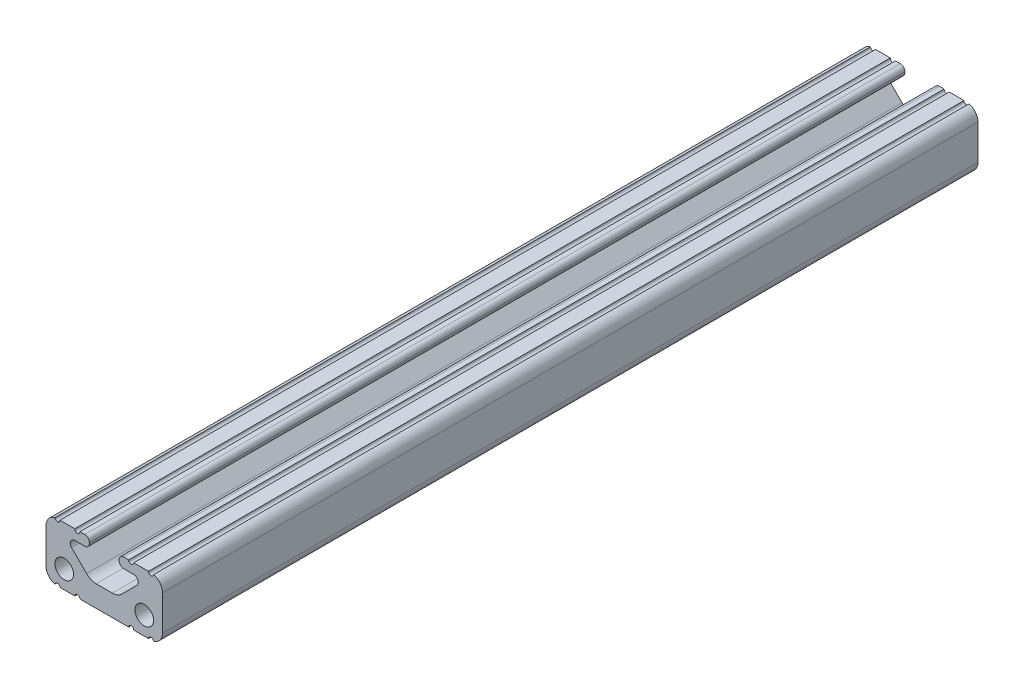
SolidWorks part; units mm, degrees
ref_plane "Front Plane" through (0, 0, 0) normal (0, 0, 1) x (1, 0, 0)
ref_plane "Top Plane" through (0, 0, 0) normal (0, 1, 0) x (1, 0, 0)
ref_plane "Right Plane" through (0, 0, 0) normal (1, 0, 0) x (0, 0, -1)
sketch "Sketch1" plane through (0, 0, 0) normal (0, 0, 1) x (1, 0, 0)
  line L0 (0, 6.35) -> (0, -6.35) construction
  line L1 (0, -6.35) -> (12.7, -6.35)
  line L2 (12.7, -6.35) -> (12.7, 6.35)
  line L3 (12.7, 6.35) -> (3.2512, 6.35)
  line L4 (3.2512, 6.35) -> (3.2512, 4.1402)
  line L5 (3.2512, 4.1402) -> (6.4224, 4.1402)
  line L6 (7.1255, 2.4426) -> (2.9811, -1.7018)
  line L7 (2.9811, -1.7018) -> (0, -1.7018)
  circle A0 centre (8.7249, -2.3876) radius 2.032
  arc A1 (6.4224, 4.1402) -> (7.1255, 2.4426) centre (6.4224, 3.1458) cw
  dimension "Center Hole Diameter" = 4.064
  dimension "D3" = 0.9944
  dimension "Rail Height" = 25.4
  dimension "Rail Width" = 12.7
  dimension "Hole CtoC" = 17.4498
  dimension "D1" = 3.9624
  dimension "T-Slot Width" = 6.5024
  dimension "Thickness" = 2.2098
  dimension "Inner Slot Width" = 14.8336
  dimension "Slot Depth" = 5.842
  dimension "D2" = 45
sketch "Sketch2" plane through (0, 0, 0) normal (1, 0, 0) x (0, 0, -1)
  line L0 (-152.4, -6.35) -> (152.4, -6.35) construction
  line L1 (-127, 0) -> (127, 0) construction
  dimension "Length" = 304.8
sketch "Sketch3" plane through (0, 0, 0) normal (0, 0, 1) x (1, 0, 0)
  line L0 (3.2512, 6.35) -> (3.2512, 4.1402) construction
  line L1 (12.7, 6.35) -> (3.2512, 6.35) construction
  line L2 (3.2512, 4.1402) -> (6.4224, 4.1402) construction
  line L3 (3.2512, 5.3556) -> (3.2512, 5.1346)
  line L4 (12.7, -6.35) -> (12.7, 6.35) construction
  line L5 (0, -6.35) -> (12.7, -6.35) construction
  line L6 (2.9811, -1.7018) -> (0, -1.7018) construction
  line L7 (7.1255, 2.4426) -> (2.9811, -1.7018) construction
  line L8 (0, -1.7018) -> (1.7454, -1.7018)
  line L9 (4.2456, 4.1402) -> (6.4224, 4.1402)
  line L10 (3.8549, -0.828) -> (7.1255, 2.4426)
  line L11 (0, -1.7018) -> (0, -6.35)
  line L12 (0, -6.35) -> (10.16, -6.35)
  line L13 (12.7, -3.81) -> (12.7, 3.81)
  line L14 (4.2456, 6.35) -> (10.16, 6.35)
  arc A0 (3.2512, 5.3556) -> (4.2456, 6.35) centre (4.2456, 5.3556) cw
  arc A1 (3.2512, 5.1346) -> (4.2456, 4.1402) centre (4.2456, 5.1346) ccw
  arc A2 (7.1255, 2.4426) -> (6.4224, 4.1402) centre (6.4224, 3.1458) ccw construction
  arc A3 (10.16, 6.35) -> (12.7, 3.81) centre (10.16, 3.81) cw
  arc A4 (10.16, -6.35) -> (12.7, -3.81) centre (10.16, -3.81) ccw
  arc A5 (7.1255, 2.4426) -> (6.4224, 4.1402) centre (6.4224, 3.1458) ccw
  circle A6 centre (8.7249, -2.3876) radius 2.032 construction
  circle A7 centre (8.7249, -2.3876) radius 2.032
  arc A8 (1.7454, -1.7018) -> (3.8549, -0.828) centre (1.7454, 1.2814) ccw
  dimension "D2" = 2.9832
  dimension "D1" = 2.54
extrude "Boss-Extrude1" add sketch "Sketch3" along normal mid plane 304.8
sketch "Sketch4" plane through (0, 0, 0) normal (0, 0, 1) x (1, 0, 0)
  line L0 (12.7, 6.35) -> (3.2512, 6.35) construction
  line L1 (0, -6.35) -> (12.7, -6.35) construction
  line L2 (10.7569, -2.3876) -> (10.7569, 6.35) construction
  line L3 (6.4224, 3.1458) -> (6.4224, 6.35) construction
  circle A0 centre (5.8699, 6.35) radius 0.5524
  circle A1 centre (10.2045, 6.35) radius 0.5524
  circle A2 centre (5.8699, -6.35) radius 0.5524
  circle A3 centre (10.2045, -6.35) radius 0.5524
  circle A4 centre (8.7249, -2.3876) radius 2.032 construction
  dimension "D1" = 1.1049
extrude "Cut-Extrude1" cut sketch "Sketch4" against normal through all both and the other way through all
mirror "Mirror1" about plane through (0, 0, 0) normal (1, 0, 0) of bodies 135
sketch "Sketch5" plane through (0, 0, 152.4) normal (0, 0, 1) x (1, 0, 0)
  line L16 (9.652, 6.35) -> (6.4224, 6.35)
  line L17 (5.3175, 6.35) -> (4.2456, 6.35)
  line L18 (3.2512, 5.3556) -> (3.2512, 5.1346)
  line L19 (4.2456, 4.1402) -> (6.4224, 4.1402)
  line L20 (7.1255, 2.4426) -> (3.8549, -0.828)
  line L21 (1.7454, -1.7018) -> (-1.7454, -1.7018)
  line L22 (-3.8549, -0.828) -> (-7.1255, 2.4426)
  line L23 (-6.4224, 4.1402) -> (-4.2456, 4.1402)
  line L24 (-3.2512, 5.1346) -> (-3.2512, 5.3556)
  line L25 (-4.2456, 6.35) -> (-5.3175, 6.35)
  line L26 (-6.4224, 6.35) -> (-9.652, 6.35)
  line L27 (-12.7, 3.81) -> (-12.7, -3.81)
  line L28 (-9.652, -6.35) -> (-6.4224, -6.35)
  line L29 (-5.3175, -6.35) -> (5.3175, -6.35)
  line L30 (6.4224, -6.35) -> (9.652, -6.35)
  line L31 (12.7, -3.81) -> (12.7, 3.81)
  line L32 (9.652, 6.35) -> (6.4224, 6.35)
  line L33 (5.3175, 6.35) -> (4.2456, 6.35)
  line L34 (3.2512, 5.3556) -> (3.2512, 5.1346)
  line L35 (4.2456, 4.1402) -> (6.4224, 4.1402)
  line L36 (7.1255, 2.4426) -> (3.8549, -0.828)
  line L37 (1.7454, -1.7018) -> (-1.7454, -1.7018)
  line L38 (-3.8549, -0.828) -> (-7.1255, 2.4426)
  line L39 (-6.4224, 4.1402) -> (-4.2456, 4.1402)
  line L40 (-3.2512, 5.1346) -> (-3.2512, 5.3556)
  line L41 (-4.2456, 6.35) -> (-5.3175, 6.35)
  line L42 (-6.4224, 6.35) -> (-9.652, 6.35)
  line L43 (-12.7, 3.81) -> (-12.7, -3.81)
  line L44 (-9.652, -6.35) -> (-6.4224, -6.35)
  line L45 (-5.3175, -6.35) -> (5.3175, -6.35)
  line L46 (6.4224, -6.35) -> (9.652, -6.35)
  line L47 (12.7, -3.81) -> (12.7, 3.81)
  arc A20 (12.7, 3.81) -> (10.7524, 6.2799) centre (10.16, 3.81) ccw
  arc A21 (9.652, 6.35) -> (10.7524, 6.2799) centre (10.2045, 6.35) ccw
  arc A22 (5.3175, 6.35) -> (6.4224, 6.35) centre (5.8699, 6.35) ccw
  arc A23 (4.2456, 6.35) -> (3.2512, 5.3556) centre (4.2456, 5.3556) ccw
  arc A24 (3.2512, 5.1346) -> (4.2456, 4.1402) centre (4.2456, 5.1346) ccw
  arc A25 (7.1255, 2.4426) -> (6.4224, 4.1402) centre (6.4224, 3.1458) ccw
  arc A26 (1.7454, -1.7018) -> (3.8549, -0.828) centre (1.7454, 1.2814) ccw
  arc A27 (-3.8549, -0.828) -> (-1.7454, -1.7018) centre (-1.7454, 1.2814) ccw
  arc A28 (-6.4224, 4.1402) -> (-7.1255, 2.4426) centre (-6.4224, 3.1458) ccw
  arc A29 (-4.2456, 4.1402) -> (-3.2512, 5.1346) centre (-4.2456, 5.1346) ccw
  arc A30 (-3.2512, 5.3556) -> (-4.2456, 6.35) centre (-4.2456, 5.3556) ccw
  arc A31 (-6.4224, 6.35) -> (-5.3175, 6.35) centre (-5.8699, 6.35) ccw
  arc A32 (-10.7524, 6.2799) -> (-9.652, 6.35) centre (-10.2045, 6.35) ccw
  arc A33 (-10.7524, 6.2799) -> (-12.7, 3.81) centre (-10.16, 3.81) ccw
  arc A34 (-12.7, -3.81) -> (-10.7524, -6.2799) centre (-10.16, -3.81) ccw
  arc A35 (-9.652, -6.35) -> (-10.7524, -6.2799) centre (-10.2045, -6.35) ccw
  arc A36 (-5.3175, -6.35) -> (-6.4224, -6.35) centre (-5.8699, -6.35) ccw
  arc A37 (6.4224, -6.35) -> (5.3175, -6.35) centre (5.8699, -6.35) ccw
  arc A38 (10.7524, -6.2799) -> (9.652, -6.35) centre (10.2045, -6.35) ccw
  arc A39 (10.7524, -6.2799) -> (12.7, -3.81) centre (10.16, -3.81) ccw
  arc A40 (12.7, 3.81) -> (10.7524, 6.2799) centre (10.16, 3.81) ccw
  arc A41 (9.652, 6.35) -> (10.7524, 6.2799) centre (10.2045, 6.35) ccw
  arc A42 (5.3175, 6.35) -> (6.4224, 6.35) centre (5.8699, 6.35) ccw
  arc A43 (4.2456, 6.35) -> (3.2512, 5.3556) centre (4.2456, 5.3556) ccw
  arc A44 (3.2512, 5.1346) -> (4.2456, 4.1402) centre (4.2456, 5.1346) ccw
  arc A45 (7.1255, 2.4426) -> (6.4224, 4.1402) centre (6.4224, 3.1458) ccw
  arc A46 (1.7454, -1.7018) -> (3.8549, -0.828) centre (1.7454, 1.2814) ccw
  arc A47 (-3.8549, -0.828) -> (-1.7454, -1.7018) centre (-1.7454, 1.2814) ccw
  arc A48 (-6.4224, 4.1402) -> (-7.1255, 2.4426) centre (-6.4224, 3.1458) ccw
  arc A49 (-4.2456, 4.1402) -> (-3.2512, 5.1346) centre (-4.2456, 5.1346) ccw
  arc A50 (-3.2512, 5.3556) -> (-4.2456, 6.35) centre (-4.2456, 5.3556) ccw
  arc A51 (-6.4224, 6.35) -> (-5.3175, 6.35) centre (-5.8699, 6.35) ccw
  arc A52 (-10.7524, 6.2799) -> (-9.652, 6.35) centre (-10.2045, 6.35) ccw
  arc A53 (-10.7524, 6.2799) -> (-12.7, 3.81) centre (-10.16, 3.81) ccw
  arc A54 (-12.7, -3.81) -> (-10.7524, -6.2799) centre (-10.16, -3.81) ccw
  arc A55 (-9.652, -6.35) -> (-10.7524, -6.2799) centre (-10.2045, -6.35) ccw
  arc A56 (-5.3175, -6.35) -> (-6.4224, -6.35) centre (-5.8699, -6.35) ccw
  arc A57 (6.4224, -6.35) -> (5.3175, -6.35) centre (5.8699, -6.35) ccw
  arc A58 (10.7524, -6.2799) -> (9.652, -6.35) centre (10.2045, -6.35) ccw
  arc A59 (10.7524, -6.2799) -> (12.7, -3.81) centre (10.16, -3.81) ccw
  dimension "D1" = 0
extrude "Cut-Extrude2" cut sketch "Sketch5" against normal offset from surface (127 mm away) 177.8 up to face at (0, 1.3921, -152.4)
equation "\"D3@Sketch1\"=\"Thickness@Sketch1\"*0.45"
equation "\"D1@Sketch3\"=\"Rail Width@Sketch1\"*0.2"
equation "\"D2@Sketch3\"=\"D3@Sketch1\"*3"
equation "\"D1@Boss-Extrude1\"=\"length@sketch2\""
equation "\"D1@Sketch4\"=\"Thickness@Sketch1\"*0.5"
